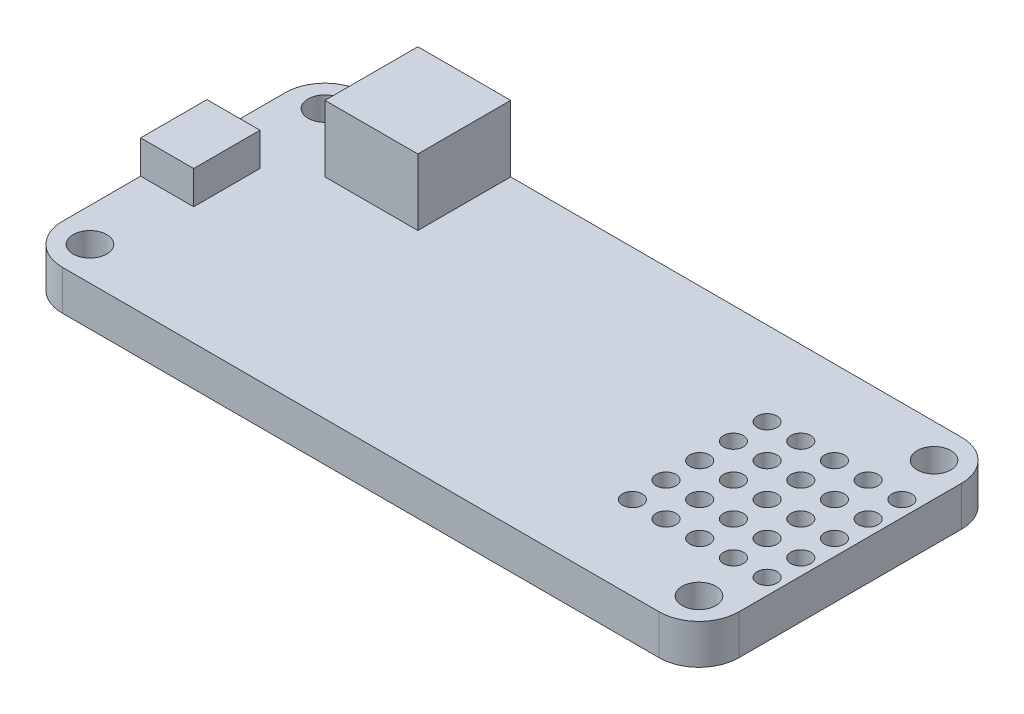
SolidWorks part; units mm, degrees
ref_plane "Front Plane" through (0, 0, 0) normal (0, 0, 1) x (1, 0, 0)
ref_plane "Top Plane" through (0, 0, 0) normal (0, 1, 0) x (1, 0, 0)
ref_plane "Right Plane" through (0, 0, 0) normal (1, 0, 0) x (0, 0, -1)
sketch "Sketch1" plane through (0, 0, 0) normal (0, 1, 0) x (1, 0, 0)
  line L0 (0, 0) -> (0, 22.8)
  line L1 (0, 22.8) -> (51, 22.8)
  line L2 (51, 22.8) -> (51, 0)
  line L3 (51, 0) -> (0, 0)
  dimension "D1" = 22.8
  dimension "D2" = 51
extrude "Boss-Extrude1" add sketch "Sketch1" along normal blind 3
sketch "Sketch2" plane through (0, 3, 0) normal (0, 1, 0) x (1, 0, 0)
  line L0 (0, 0) -> (0, 8.9)
  line L1 (0, 22.8) -> (0, 0) construction
  line L2 (0, 8.9) -> (4, 8.9)
  line L3 (4, 8.9) -> (4, 13.9)
  line L4 (4, 13.9) -> (0, 13.9)
  line L5 (0, 13.9) -> (0, 8.9)
  dimension "D1" = 5
  dimension "D2" = 4
  dimension "D3" = 8.9
extrude "Boss-Extrude2" add sketch "Sketch2" along normal blind 2.5 contours L2 L3 L4 L5
sketch "Sketch3" plane through (0, 3, 0) normal (0, 1, 0) x (1, 0, 0)
  line L0 (0, 22.8) -> (7, 22.8)
  line L1 (51, 22.8) -> (0, 22.8) construction
  line L2 (7, 22.8) -> (7, 15.8)
  line L3 (7, 15.8) -> (14, 15.8)
  line L4 (14, 15.8) -> (14, 22.8)
  line L5 (14, 22.8) -> (7, 22.8)
  line M10 (51, 22.8) -> (0, 22.8)
  dimension "D1" = 7
  dimension "D2" = 7
  dimension "D3" = 7
extrude "Boss-Extrude3" add sketch "Sketch3" along normal blind 5 contours L3 L4 L2 M10
sketch "Sketch4" plane through (0, 3, 0) normal (0, 1, 0) x (1, 0, 0)
  line L0 (0, 22.8) -> (2.54, 22.8)
  line L1 (7, 22.8) -> (0, 22.8) construction
  line L2 (2.54, 22.8) -> (2.54, 20.26)
  line L3 (0, 0) -> (2.54, 0)
  line L4 (2.54, 0) -> (2.54, 2.54)
  line L5 (51, 22.8) -> (48.46, 22.8)
  line L6 (48.46, 22.8) -> (48.46, 20.26)
  line L7 (51, 0) -> (48.46, 0)
  line L8 (48.46, 0) -> (48.46, 2.54)
  line L9 (0, 8.9) -> (0, 0) construction
  line L10 (0, 0) -> (51, 0) construction
  circle A0 centre (2.54, 20.26) radius 1.27
  circle A1 centre (2.54, 2.54) radius 1.27
  circle A2 centre (48.46, 20.26) radius 1.27
  circle A3 centre (48.46, 2.54) radius 1.27
  dimension "D1" = 2.54
  dimension "D9" = 2.54
  dimension "D10" = 2.54
  dimension "D11" = 2.54
  dimension "D12" = 2.54
  dimension "D2" = 2.54
  dimension "D3" = 2.54
  dimension "D4" = 2.54
  dimension "D5" = 2.54
  dimension "D6" = 2.54
  dimension "D7" = 2.54
  dimension "D8" = 2.54
extrude "Cut-Extrude1" cut sketch "Sketch4" against normal through all
fillet "Fillet1" radius 3 4 edges at (51, 1.5, -22.8) (51, 1.5, 0) (0, 1.5, -22.8) (0, 1.5, 0)
sketch "Sketch5" plane through (0, 3, 0) normal (0, 1, 0) x (1, 0, 0)
  line L0 (48.46, 2.54) -> (48.46, 20.26)
  circle A0 centre (49.8131, 6.32) radius 0.75
  circle A1 centre (47.2731, 6.32) radius 0.75
  circle A2 centre (44.7331, 6.32) radius 0.75
  circle A3 centre (42.1931, 6.32) radius 0.75
  circle A4 centre (39.6531, 6.32) radius 0.75
  circle A5 centre (49.8131, 8.86) radius 0.75
  circle A6 centre (39.6531, 8.86) radius 0.75
  circle A7 centre (42.1931, 8.86) radius 0.75
  circle A8 centre (44.7331, 8.86) radius 0.75
  circle A9 centre (47.2731, 8.86) radius 0.75
  circle A10 centre (49.8131, 11.4) radius 0.75
  circle A11 centre (39.6531, 11.4) radius 0.75
  circle A12 centre (42.1931, 11.4) radius 0.75
  circle A13 centre (44.7331, 11.4) radius 0.75
  circle A14 centre (47.2731, 11.4) radius 0.75
  circle A15 centre (49.8131, 13.94) radius 0.75
  circle A16 centre (39.6531, 13.94) radius 0.75
  circle A17 centre (42.1931, 13.94) radius 0.75
  circle A18 centre (44.7331, 13.94) radius 0.75
  circle A19 centre (47.2731, 13.94) radius 0.75
  circle A20 centre (49.8131, 16.48) radius 0.75
  circle A21 centre (39.6531, 16.48) radius 0.75
  circle A22 centre (42.1931, 16.48) radius 0.75
  circle A23 centre (44.7331, 16.48) radius 0.75
  circle A24 centre (47.2731, 16.48) radius 0.75
  point P4 (48.46, 6.32)
  point P5 (0, 0)
  point P6 (0, 0)
  point P7 (0, 0)
  point P8 (0, 0)
  point P9 (0, 0)
  point P12 (0, 0)
  point P13 (0, 0)
  point P62 (0, 0)
  point P63 (0, 0)
  point P64 (0, 0)
  point P65 (0, 0)
  point P66 (0, 0)
  point P67 (0, 0)
  point P68 (0, 0)
  dimension "D7" = 1.5
  dimension "D1" = 3.78
  dimension "D8" = 5
  dimension "D9" = 5
extrude "Cut-Extrude2" cut sketch "Sketch5" against normal through all contours A1 | A5 | A23 | A4 | A3 | A2 | A0 | A9 | A8 | A7 | A6 | A11 | A12 | A13 | A14 | A10 | A15 | A19 | A18 | A17 | A16 | A21 | A22 | A24 | A20
